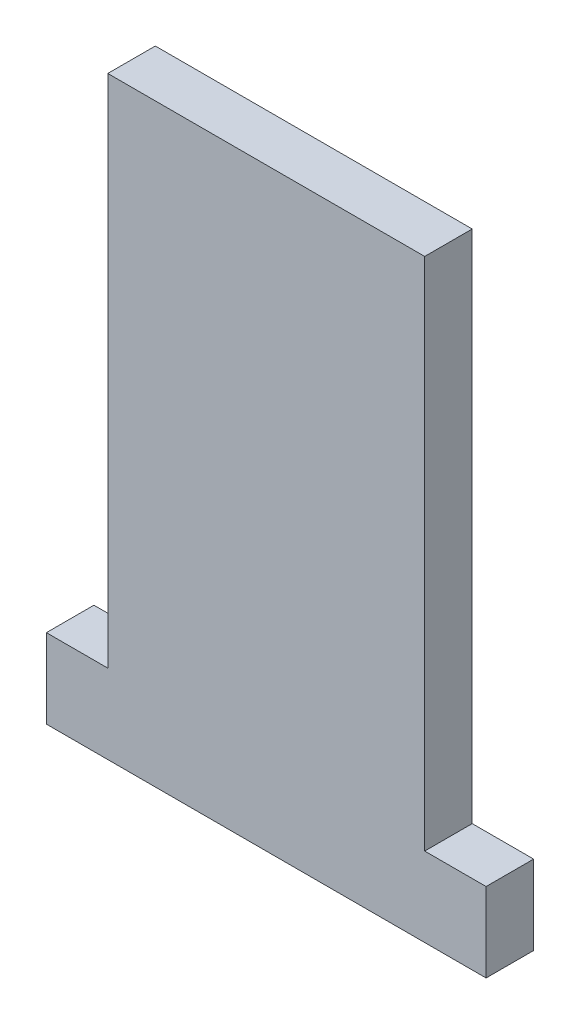
SolidWorks part; units mm, degrees
ref_plane "Front Plane" through (0, 0, 0) normal (0, 0, 1) x (1, 0, 0)
ref_plane "Top Plane" through (0, 0, 0) normal (0, 1, 0) x (1, 0, 0)
ref_plane "Right Plane" through (0, 0, 0) normal (1, 0, 0) x (0, 0, -1)
sketch "Sketch1" plane through (0, 0, 0) normal (0, 0, 1) x (1, 0, 0)
  line L1 (-4, 6.5) -> (4, 6.5)
  line L2 (-4, 6.5) -> (-4, -6.5)
  line L3 (-4, -6.5) -> (4, -6.5)
  line L4 (4, 6.5) -> (4, -6.5)
  line L5 (-4, 6.5) -> (4, -6.5) construction
  line L6 (-4, -6.5) -> (4, 6.5) construction
  point P0 (0, 0)
  dimension "D1" = 8
  dimension "D2" = 13
extrude "Boss-Extrude1" add sketch "Sketch1" along normal mid plane 1.2
sketch "Sketch2" plane through (0, 0, 0.6) normal (0, 0, 1) x (1, 0, 0)
  line L0 (-4, -6.5) -> (4, -6.5) construction
  line L1 (-5.55, -8.5) -> (5.55, -8.5)
  line L2 (-5.55, -8.5) -> (-5.55, -6.5)
  line L3 (-5.55, -6.5) -> (5.55, -6.5)
  line L4 (5.55, -8.5) -> (5.55, -6.5)
  line L5 (-5.55, -8.5) -> (5.55, -6.5) construction
  line L6 (-5.55, -6.5) -> (5.55, -8.5) construction
  point P0 (0, -7.5)
  point P7 (0, 0)
  dimension "D1" = 11.1
  dimension "D2" = 2
extrude "Boss-Extrude2" add sketch "Sketch2" against normal up to surface (1.2 mm away) up to face at (0, 0, -0.6)
